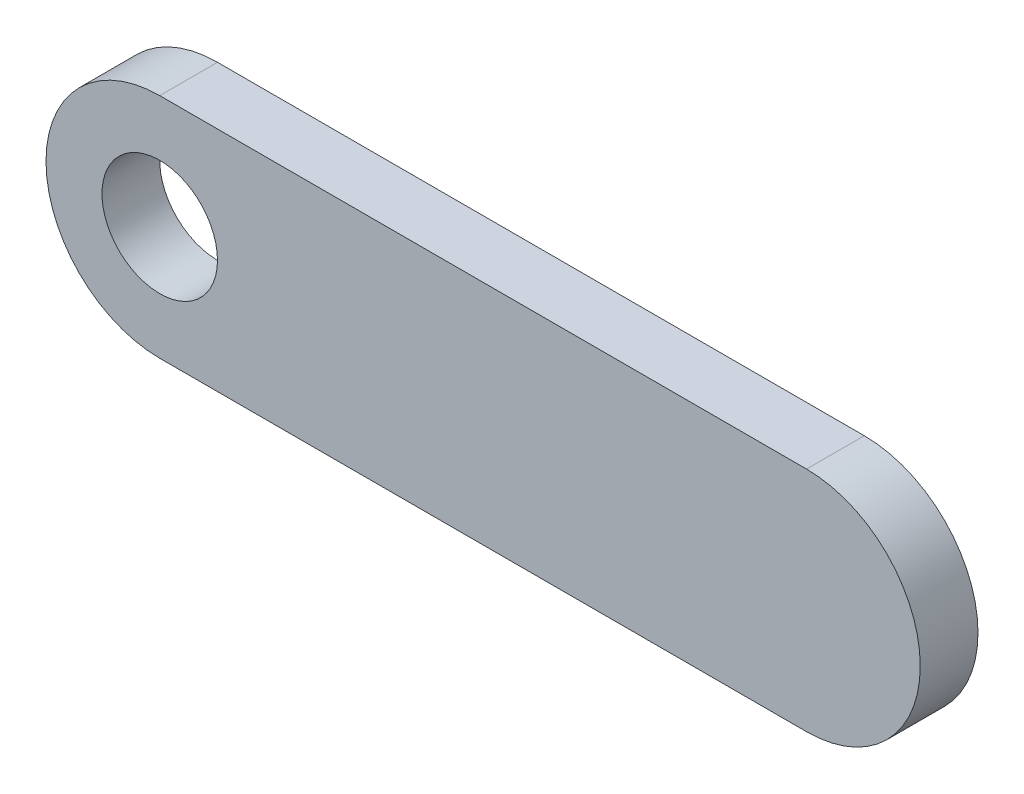
SolidWorks part; units mm, degrees
ref_plane "Front Plane" through (0, 0, 0) normal (0, 0, 1) x (1, 0, 0)
ref_plane "Top Plane" through (0, 0, 0) normal (0, 1, 0) x (1, 0, 0)
ref_plane "Right Plane" through (0, 0, 0) normal (1, 0, 0) x (0, 0, -1)
sketch "Sketch2" plane through (0, 0, 0) normal (0, 0, 1) x (1, 0, 0)
  line L0 (0, 0) -> (280, 0) construction
  line L1 (0, 49.2347) -> (280, 49.2347)
  line L2 (0, -49.2347) -> (280, -49.2347)
  arc A2 (0, 49.2347) -> (0, -49.2347) centre (0, 0) ccw
  arc A3 (280, -49.2347) -> (280, 49.2347) centre (280, 0) ccw
  circle A4 centre (0, 0) radius 25
  point P1 (280, -49.2347)
  point P3 (140, 0)
  point P9 (0, 0)
  point P10 (0, 0)
  dimension "D1" = 280
  dimension "D2" = 50
extrude "Boss-Extrude2" add sketch "Sketch2" along normal blind 25
